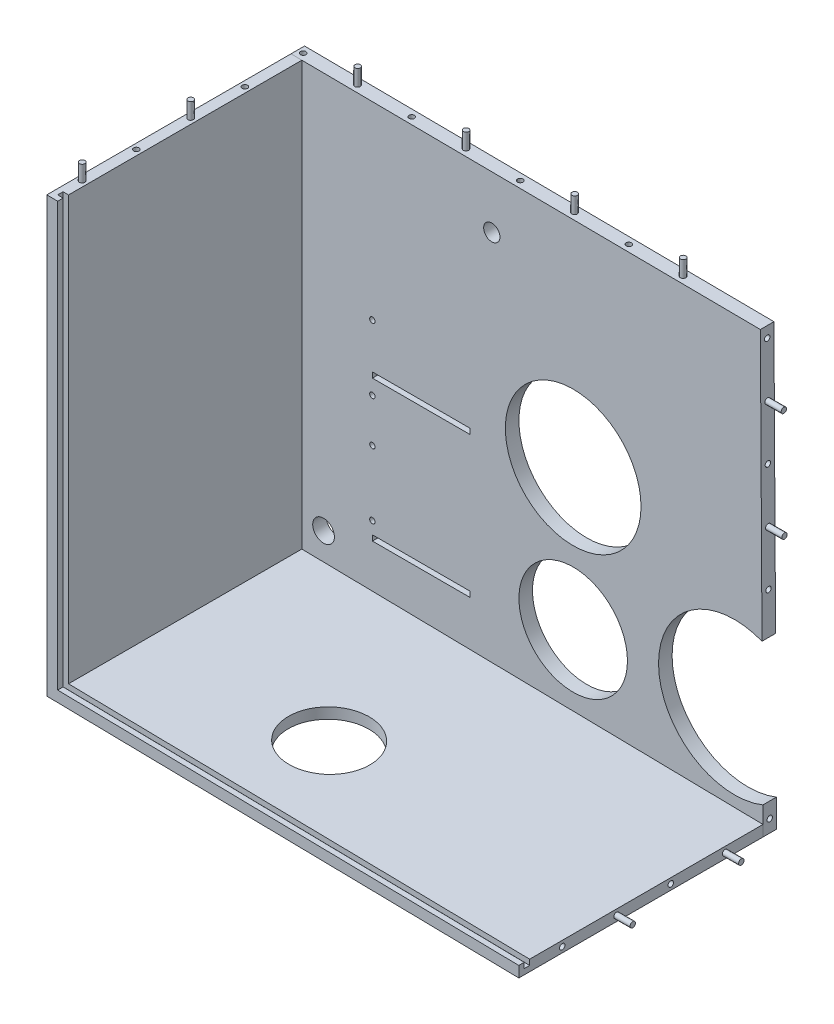
SolidWorks part; units mm, degrees
ref_plane "Alzado" through (0, 0, 0) normal (0, 0, 1) x (1, 0, 0)
ref_plane "Planta" through (0, 0, 0) normal (0, 1, 0) x (1, 0, 0)
ref_plane "Vista lateral" through (0, 0, 0) normal (1, 0, 0) x (0, 0, -1)
sketch "Croquis1" plane through (0, 0, 0) normal (0, 0, 1) x (1, 0, 0)
  line L0 (-86, 80) -> (86, 80) construction
  line L1 (-86, -80) -> (87.9743, -82.988) construction
  line L2 (-86, 80) -> (-86, -80) construction
  line L3 (86, 80) -> (87.9743, -82.988) construction
  line L4 (55, 0) -> (-55, 0) construction
  line L5 (0, -55) -> (0, 55) construction
  line L6 (0, 80) -> (0.9872, -81.494) construction
  line L7 (-86, 0) -> (86.9872, -1.494) construction
  point P1 (0, 80)
  point P3 (-86, 0)
  point P4 (86.9872, -1.494)
  point P5 (0.9872, -81.494)
  dimension "D1" = 174
  dimension "D2" = 172
  dimension "D3" = 160
  dimension "D4" = 163
sketch "Croquis2" plane through (0, 0, 0) normal (0, 0, 1) x (1, 0, 0)
  line L0 (76.1204, 70) -> (2.1204, 70) construction
  line L1 (2.1204, 70) -> (2.1204, -32) construction
  line L2 (2.1204, -32) -> (76.1204, -32) construction
  line L3 (76.1204, -32) -> (76.1204, 70) construction
  line L4 (-86, 80) -> (86, 80) construction
  line L5 (86, 80) -> (87.9743, -82.988) construction
  point P13 (76.1204, 70)
  dimension "D1" = 102
  dimension "D2" = 10
  dimension "D3" = 10
  dimension "D4" = 74
sketch "Croquis3" plane through (0, 0, 0) normal (0, 0, 1) x (1, 0, 0)
  line L0 (-86, 80) -> (86, 80) construction
  line L1 (-86, 80) -> (-86, -80) construction
  line L2 (-81, 70) -> (-19, 70) construction
  line L3 (-19, 70) -> (-19, -25) construction
  line L4 (-19, -25) -> (-81, -25) construction
  line L5 (-81, -25) -> (-81, 70) construction
  line L6 (-19, 58) -> (2.1204, 58) construction
  line L7 (2.1204, 70) -> (2.1204, -32) construction
  line L8 (2.1204, -47) -> (-19, -47) construction
  line L9 (-19, -47) -> (-19, -25) construction
  line L10 (2.1204, -32) -> (2.1204, -47) construction
  point P0 (-81, 70)
  dimension "D1" = 10
  dimension "D2" = 5
  dimension "D3" = 62
  dimension "D4" = 95
  dimension "D5" = 22
  dimension "D6" = 105
sketch "Croquis4" plane through (0, 0, 0) normal (0, 0, 1) x (1, 0, 0)
  line L0 (2.1204, -32) -> (76.1204, -32) construction
  line L1 (22.6942, -40) -> (42.6942, -40) construction
  line L2 (22.6942, -40) -> (22.6942, -41) construction
  line L3 (22.6942, -41) -> (42.6942, -41) construction
  line L4 (72.6942, -41) -> (72.6942, -40) construction
  line L5 (22.6942, -62) -> (42.6942, -62) construction
  line L6 (72.6942, -62) -> (72.6942, -63) construction
  line L7 (72.6942, -63) -> (52.6942, -63) construction
  line L8 (22.6942, -63) -> (22.6942, -62) construction
  line L9 (42.6942, -40) -> (42.6942, -41) construction
  line L11 (52.6942, -63) -> (52.6942, -62) construction
  line L12 (52.6942, -40) -> (72.6942, -40) construction
  line L13 (52.6942, -41) -> (72.6942, -41) construction
  line L14 (42.6942, -62) -> (42.6942, -63) construction
  line L15 (52.6942, -41) -> (52.6942, -40) construction
  line L16 (52.6942, -62) -> (72.6942, -62) construction
  line L17 (42.6942, -63) -> (22.6942, -63) construction
  point P8 (42.6942, -40)
  point P11 (52.6942, -40)
  dimension "D1" = 50
  dimension "D2" = 8
  dimension "D3" = 1
  dimension "D4" = 1
  dimension "D5" = 23
  dimension "D6" = 50
  dimension "D7" = 20
  dimension "D8" = 20
sketch "Croquis6" plane through (0, 0, 0) normal (0, 0, 1) x (1, 0, 0)
  line L0 (-19, -25) -> (-81, -25) construction
  line L1 (-19, -47) -> (-19, -25) construction
  circle A0 centre (-34, -40) radius 12.5 construction
  dimension "D1" = 25
  dimension "D2" = 15
  dimension "D3" = 15
sketch "Croquis7" plane through (0, 0, 0) normal (0, 0, 1) x (1, 0, 0)
  line L0 (2.1204, 70) -> (2.1204, -32) construction
  circle A0 centre (-7.8796, 69.2) radius 7.5 construction
  dimension "D1" = 10
  dimension "D2" = 15
sketch "Croquis8" plane through (0, 0, 0) normal (0, 0, 1) x (1, 0, 0)
  line L0 (-86, -80) -> (87.9743, -82.988) construction
  line L1 (-86, 80) -> (-86, -80) construction
  line L2 (85.9495, -80.953) -> (-84, -78.0341) construction
  line L3 (86, 80) -> (87.9743, -82.988) construction
  line L8 (-84, -78.0341) -> (-84, 78) construction
  line L9 (-84, 78) -> (84.0241, 78) construction
  line L10 (84.0241, 78) -> (85.9495, -80.953) construction
  line L11 (-86, 80) -> (86, 80) construction
  dimension "D1" = 2
  dimension "D2" = 2
  dimension "D3" = 2
  dimension "D4" = 2
sketch "Croquis9" plane through (0, 0, 0) normal (0, 0, 1) x (1, 0, 0)
  line L0 (-71, -25) -> (-71, -78.2573) construction
  line L1 (-86, 80) -> (-86, -80) construction
  line L4 (85.9495, -80.953) -> (-84, -78.0341) construction
  line L5 (-19, -25) -> (-81, -25) construction
  circle A0 centre (-71, -35) radius 0.5 construction
  circle A1 centre (-71, -47) radius 0.5 construction
  circle A2 centre (-71, -55) radius 0.5 construction
  circle A3 centre (-71, -67) radius 0.5 construction
  point P4 (-71, -35)
  point P9 (-71, -47)
  point P10 (-71, -55)
  point P11 (-71, -67)
  dimension "D6" = 1
  dimension "D7" = 1
  dimension "D8" = 1
  dimension "D9" = 1
  dimension "D1" = 15
  dimension "D2" = 10
  dimension "D3" = 12
  dimension "D4" = 8
  dimension "D5" = 12
sketch "Croquis10" plane through (0, 0, 0) normal (0, 0, 1) x (1, 0, 0)
  line L0 (-71, -25) -> (-71, -78.2573) construction
  line L1 (-86, -80) -> (87.9743, -82.988) construction
  line L2 (-53, -43.2562) -> (-71, -43.2562) construction
  line L3 (-53, -70.2562) -> (-71, -70.2562) construction
  line L4 (-71, -70.2562) -> (-71, -69.2562) construction
  line L5 (-71, -69.2562) -> (-53, -69.2562) construction
  line L6 (-53, -69.2562) -> (-53, -70.2562) construction
  line L7 (-71, -43.2562) -> (-71, -44.2562) construction
  line L8 (-71, -44.2562) -> (-53, -44.2562) construction
  line L9 (-53, -44.2562) -> (-53, -43.2562) construction
  line L10 (-86, 80) -> (-86, -80) construction
  point P0 (-71, -70.2562)
  point P1 (-71, -43.2562)
  dimension "D1" = 27
  dimension "D2" = 10
  dimension "D3" = 1
  dimension "D4" = 1
  dimension "D5" = 18
  dimension "D6" = 18
  dimension "D7" = 15
  dimension "D8" = 15
sketch "Croquis11" plane through (0, 0, 0) normal (0, 0, 1) x (1, 0, 0)
  line L0 (-86, -80) -> (87.9743, -82.988) construction
  line L1 (84.0241, 78) -> (85.9495, -80.953) construction
  line L2 (-86, 80) -> (-86, -80) construction
  circle A0 centre (-4.2697, -63.4011) radius 14 construction
  circle A1 centre (-34, -65.8909) radius 10 construction
  dimension "D1" = 18
  dimension "D2" = 28
  dimension "D4" = 20
  dimension "D3" = 90
  dimension "D5" = 15
  dimension "D6" = 52
sketch "Croquis12" plane through (0, 0, 0) normal (0, 0, 1) x (1, 0, 0)
  line L0 (-86, 80) -> (86, 80) construction
  line L1 (-86, 80) -> (-86, -80) construction
  line L3 (86, 80) -> (87.9743, -82.988) construction
  line L4 (-86, -80) -> (87.9743, -82.988) construction
  circle A0 centre (-80, -73.102) radius 2 construction
  circle A1 centre (-80, 74) radius 2 construction
  circle A2 centre (79.0722, 74) radius 2 construction
  circle A3 centre (80.8997, -76.8656) radius 2 construction
  point P0 (-80, 74)
  point P1 (79.0722, 74)
  point P2 (80.8997, -76.8656)
  point P3 (-80, -73.102)
  dimension "D1" = 6
  dimension "D2" = 6
  dimension "D3" = 6
  dimension "D4" = 7
  dimension "D5" = 7
  dimension "D6" = 6
  dimension "D7" = 7
  dimension "D8" = 6
sketch "Croquis13" plane through (0, 0, 0) normal (0, 0, 1) x (1, 0, 0)
  line L0 (76.1204, 70) -> (2.1204, 70) construction
  line L1 (76.1204, -32) -> (76.1204, 70) construction
  line L2 (2.1204, -32) -> (76.1204, -32) construction
  circle A0 centre (72.1204, 63) radius 1.5 construction
  circle A1 centre (72.1204, -26) radius 1.5 construction
  point P0 (72.1204, 63)
  point P7 (72.1204, -26)
  dimension "D3" = 3
  dimension "D6" = 3
  dimension "D1" = 7
  dimension "D2" = 4
  dimension "D4" = 89
  dimension "D5" = 6
sketch "Croquis14" plane through (0, 0, 0) normal (0, 0, 1) x (1, 0, 0)
  line L1 (-19, 70) -> (-19, -25) construction
  line L2 (-19, -25) -> (-81, -25) construction
  circle A0 centre (-49, 45) radius 1.5 construction
  circle A1 centre (-49, -10) radius 1.5 construction
  point P0 (-49, 45)
  point P1 (-49, -10)
  dimension "D3" = 3
  dimension "D4" = 3
  dimension "D1" = 30
  dimension "D2" = 30
  dimension "D5" = 55
  dimension "D6" = 15
sketch "Croquis15" plane through (0, 0, 0) normal (0, 0, 1) x (1, 0, 0)
  line L0 (0.4936, -0.747) -> (-86, 0)
  line L1 (0, 80) -> (0.9872, -81.494) construction
  line L2 (-86, 0) -> (-86, -80)
  line L3 (-86, -80) -> (0.9872, -81.494)
  line L4 (0.9872, -81.494) -> (0.4936, -0.747)
extrude "Saliente-Extruir1" add sketch "Croquis15" along normal blind 2.5
sketch "Croquis16" plane through (0, 0, 2.5) normal (0, 0, 1) x (1, 0, 0)
  line L0 (-84, -0.017) -> (-84, -78.0341)
  line L1 (-84, -78.0341) -> (-84, 78) construction
  line L2 (-84, -78.0341) -> (0.9748, -79.4935)
  line L3 (85.9495, -80.953) -> (-84, -78.0341) construction
  line L4 (0.9748, -79.4935) -> (0.9872, -81.494)
  line L5 (0.9872, -81.494) -> (-86, -80)
  line L6 (-86, -80) -> (-86, 0)
  line L7 (-86, 0) -> (-84, -0.017)
extrude "Saliente-Extruir2" add sketch "Croquis16" along normal blind 45
sketch "Croquis17" plane through (0, 0, 2.5) normal (0, 0, 1) x (1, 0, 0)
  line L0 (0.7968, -50.35) -> (0.956, -76.3893)
  line L1 (-71, -43.2562) -> (-53, -43.2562)
  line L2 (-71, -43.2562) -> (-71, -44.2562)
  line L3 (-71, -44.2562) -> (-53, -44.2562)
  line L4 (-53, -43.2562) -> (-53, -44.2562)
  line L5 (-71, -69.2562) -> (-53, -69.2562)
  line L6 (-71, -69.2562) -> (-71, -70.2562)
  line L7 (-71, -70.2562) -> (-53, -70.2562)
  line L8 (-53, -69.2562) -> (-53, -70.2562)
  circle A0 centre (-34, -40) radius 12.5
  arc A1 (0.7968, -50.35) -> (0.956, -76.3893) centre (-4.2697, -63.4011) ccw
  circle A2 centre (-34, -65.8909) radius 10
  circle A3 centre (-80, -73.102) radius 2
  circle A4 centre (-71, -67) radius 0.5
  circle A5 centre (-71, -55) radius 0.5
  circle A6 centre (-71, -47) radius 0.5
  circle A7 centre (-71, -35) radius 0.5
  circle A8 centre (-49, -10) radius 1.5
extrude "Cortar-Extruir1" cut sketch "Croquis17" against normal blind 45
sketch "Croquis18" plane through (-84, 0, 0) normal (1, 0, 0) x (0, 0, -1)
  line L0 (-47.5, -78.0341) -> (-2.5, -78.0341) construction
  line L1 (-46.5, -78.0341) -> (-45.5, -78.0341)
  line L2 (-46.5, -78.0341) -> (-46.5, -0.017)
  line L3 (-46.5, -0.017) -> (-45.5, -0.017)
  line L4 (-45.5, -78.0341) -> (-45.5, -0.017)
  line L5 (-47.5, -0.017) -> (-2.5, -0.0172) construction
  line L6 (-47.5, -78.0341) -> (-47.5, -0.017) construction
  dimension "D1" = 1
  dimension "D2" = 1
extrude "Cortar-Extruir2" cut sketch "Croquis18" against normal blind 1
sketch "Croquis19" plane through (-0.0062, -0.7321, 0) normal (0.0085, 1, 0) x (1, -0.0085, 0)
  line L1 (-83.9968, -46.5) -> (-84.9968, -46.5)
  line L2 (-83.9968, -46.5) -> (-83.9968, -45.5)
  line L3 (-83.9968, -45.5) -> (-84.9968, -45.5)
  line L4 (-84.9968, -46.5) -> (-84.9968, -45.5)
  dimension "D1" = 1
  dimension "D2" = 1
extrude "Cortar-Extruir3" cut sketch "Croquis19" against normal blind 1
sketch "Croquis20" plane through (0, -78.0341, 0) normal (0, 1, 0) x (1, 0, 0)
  line L0 (-85, -46.5) -> (-85, -45.5) construction
  line L1 (-84, -45.5) -> (-85, -45.5)
  line L2 (-84, -45.5) -> (-84, -46.5)
  line L3 (-84, -46.5) -> (-85, -46.5)
  line L4 (-85, -45.5) -> (-85, -46.5)
extrude "Cortar-Extruir4" cut sketch "Croquis20" against normal blind 1
sketch "Croquis21" plane through (-1.3646, -79.4533, 0) normal (0.0172, 0.9999, 0) x (0.9999, -0.0172, 0)
  line L0 (2.3397, -47.5) -> (2.3398, -2.5) construction
  line L1 (-82.6476, -45.5) -> (2.3397, -45.5)
  line L2 (-82.6476, -45.5) -> (-82.6476, -46.5)
  line L3 (-82.6476, -46.5) -> (2.3397, -46.5)
  line L5 (2.3397, -45.5) -> (2.8937, -45.5)
  line L6 (2.8937, -45.5) -> (2.8937, -46.5)
  line L7 (2.8937, -46.5) -> (2.3397, -46.5)
  dimension "D1" = 1
extrude "Cortar-Extruir5" cut sketch "Croquis21" against normal blind 1
sketch "Croquis24" plane through (0.489, 0.003, 0) normal (1, 0.0061, 0) x (0, 0, -1)
  line L0 (0, -76.3937) -> (-2.5, -76.3937) construction
  line L1 (-2.5, -0.75) -> (0, -0.75) construction
  circle A0 centre (-1.25, -79.1937) radius 0.5
  circle A1 centre (-1.25, -2.75) radius 0.5
  circle A2 centre (-1.25, -22.75) radius 0.5
  circle A3 centre (-1.25, -42.75) radius 0.5
  dimension "D1" = 2.8
  dimension "D2" = 2
  dimension "D3" = 20
  dimension "D4" = 20
extrude "Cortar-Extruir13" cut sketch "Croquis24" against normal blind 4
sketch "Croquis25" plane through (0.489, 0.003, 0) normal (1, 0.0061, 0) x (0, 0, -1)
  line L0 (-2.5, -0.75) -> (0, -0.75) construction
  circle A0 centre (-1.25, -12.75) radius 0.5
  circle A1 centre (-1.25, -32.75) radius 0.5
  dimension "D1" = 12
  dimension "D2" = 20
extrude "Saliente-Extruir3" add sketch "Croquis25" along normal blind 3
sketch "Croquis26" plane through (0.4821, 0.003, 0) normal (1, 0.0062, 0) x (0, 0, -1)
  line L0 (-2.5, -81.4986) -> (-2.5, -79.498) construction
  circle A0 centre (-29.5, -80.4983) radius 0.5
  circle A1 centre (-9.5, -80.4983) radius 0.5
  dimension "D1" = 20
  dimension "D2" = 7
extrude "Saliente-Extruir4" add sketch "Croquis26" along normal blind 3
sketch "Croquis27" plane through (0.4821, 0.003, 0) normal (1, 0.0062, 0) x (0, 0, -1)
  line L0 (-2.5, -81.4986) -> (-2.5, -79.498) construction
  circle A0 centre (-39.5, -80.4983) radius 0.5
  circle A1 centre (-19.5, -80.4983) radius 0.5
  dimension "D1" = 20
  dimension "D2" = 17
extrude "Cortar-Extruir14" cut sketch "Croquis27" against normal blind 4
sketch "Croquis28" plane through (-1.399, -81.453, 0) normal (-0.0172, -0.9999, 0) x (0.9999, -0.0172, 0)
  circle A0 centre (-50.1135, 30) radius 7.5
  dimension "D5" = 15
extrude "Cortar-Extruir15" cut sketch "Croquis28" against normal blind 45
sketch "Croquis29" plane through (-86, 0, 0) normal (-1, 0, 0) x (0, 0, 1)
  line L0 (10.5233, 0) -> (10.5233, -80) construction
  line L1 (47.5, 0) -> (2.5, 0) construction
  line L2 (47.5, -80) -> (0, -80) construction
  text T0 "USB" font "Century Gothic" height 25
extrude "Cortar-Extruir16" cut sketch "Croquis29" against normal blind 1
sketch "Croquis30" plane through (-0.0064, -0.7427, 0) normal (0.0086, 1, 0) x (1, -0.0086, 0)
  line L0 (-85.9968, -2.5) -> (-85.9968, 0) construction
  circle A0 centre (-84.9968, -1.25) radius 0.5
  circle A1 centre (-64.9968, -1.25) radius 0.5
  circle A2 centre (-44.9968, -1.25) radius 0.5
  circle A3 centre (-24.9968, -1.25) radius 0.5
  dimension "D1" = 1
  dimension "D2" = 20
  dimension "D3" = 20
  dimension "D4" = 20
extrude "Cortar-Extruir17" cut sketch "Croquis30" against normal blind 4
sketch "Croquis31" plane through (-0.0064, -0.7427, 0) normal (0.0086, 1, 0) x (1, -0.0086, 0)
  line L0 (-85.9968, -2.5) -> (-85.9968, 0) construction
  circle A0 centre (-74.9968, -1.25) radius 0.5
  circle A1 centre (-54.9968, -1.25) radius 0.5
  circle A2 centre (-34.9968, -1.25) radius 0.5
  circle A3 centre (-14.9968, -1.25) radius 0.5
  dimension "D1" = 11
  dimension "D4" = 20
  dimension "D2" = 20
  dimension "D3" = 20
extrude "Saliente-Extruir5" add sketch "Croquis31" along normal blind 3
sketch "Croquis32" plane through (-0.0062, -0.7321, 0) normal (0.0085, 1, 0) x (1, -0.0085, 0)
  line L0 (-84.9968, -47.5) -> (-84.9968, -2.6047) construction
  line L1 (-83.9968, -47.5) -> (-85.9969, -47.5) construction
  line L2 (-85.9969, 0) -> (86.9967, 0) construction
  circle A0 centre (-84.9968, -12) radius 0.5
  circle A1 centre (-84.9968, -32) radius 0.5
  dimension "D1" = 12
  dimension "D3" = 20
extrude "Cortar-Extruir18" cut sketch "Croquis32" against normal blind 4
sketch "Croquis33" plane through (-0.0062, -0.7321, 0) normal (0.0085, 1, 0) x (1, -0.0085, 0)
  line L0 (0.4999, 0) -> (-85.9969, 0) construction
  circle A0 centre (-84.9968, -22) radius 0.5
  circle A1 centre (-84.9968, -42) radius 0.5
  dimension "D1" = 22
  dimension "D2" = 20
extrude "Saliente-Extruir6" add sketch "Croquis33" along normal blind 3
